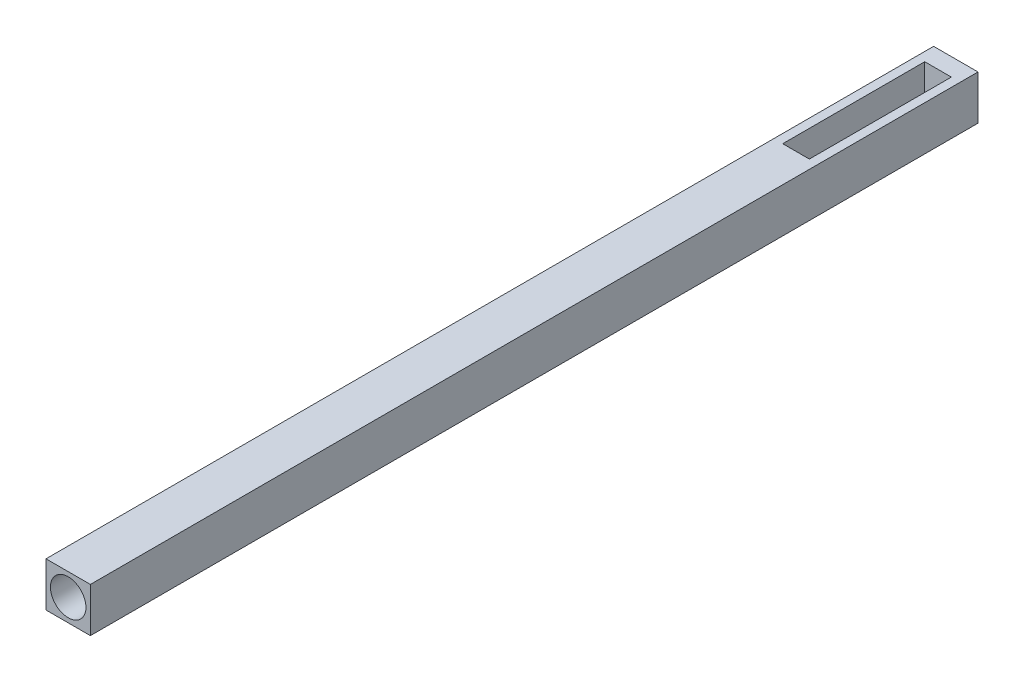
SolidWorks part; units mm, degrees
material "PET"
ref_plane "Front Plane" through (0, 0, 0) normal (0, 0, 1) x (1, 0, 0)
ref_plane "Top Plane" through (0, 0, 0) normal (0, 1, 0) x (1, 0, 0)
ref_plane "Right Plane" through (0, 0, 0) normal (1, 0, 0) x (0, 0, -1)
sketch "Sketch1" plane through (0, 0, 0) normal (0, 1, 0) x (1, 0, 0)
  line L0 (-1.5875, 38.1) -> (1.5875, 25.4) construction
  line L1 (-1.5875, 25.4) -> (1.5875, 25.4) construction
  line L2 (-1.5875, 25.4) -> (-1.5875, -25.4)
  line L3 (-1.5875, -25.4) -> (1.5875, -25.4)
  line L4 (1.5875, 25.4) -> (1.5875, -25.4)
  line L5 (-1.5875, 25.4) -> (1.5875, -25.4) construction
  line L6 (-1.5875, -25.4) -> (1.5875, 25.4) construction
  line L7 (-1.5875, 25.4) -> (1.5875, 25.4) construction
  line L8 (-1.5875, 25.4) -> (-1.5875, 38.1)
  line L9 (-1.5875, 38.1) -> (1.5875, 38.1)
  line L10 (1.5875, 25.4) -> (1.5875, 38.1)
  line L11 (0.9525, 26.67) -> (-0.9525, 26.67)
  line L12 (0.9525, 26.67) -> (0.9525, 36.83)
  line L13 (0.9525, 36.83) -> (-0.9525, 36.83)
  line L14 (-0.9525, 26.67) -> (-0.9525, 36.83)
  line L15 (0.9525, 26.67) -> (-0.9525, 36.83) construction
  line L16 (0.9525, 36.83) -> (-0.9525, 26.67) construction
  line L17 (-1.5875, 25.4) -> (1.5875, 38.1) construction
  point P0 (0, 0)
  point P4 (0, 31.75)
  point P14 (0, 31.75)
  dimension "D1" = 3.175
  dimension "D2" = 50.8
  dimension "D3" = 12.7
  dimension "D4" = 10.16
  dimension "D5" = 1.905
extrude "Boss-Extrude2" add sketch "Sketch1" along normal blind 3.175
sketch "Sketch2" plane through (0, 0, 25.4) normal (0, 0, 1) x (1, 0, 0)
  line L0 (-1.5875, 3.175) -> (1.5875, 0) construction
  line L1 (-1.5875, 0) -> (1.5875, 3.175) construction
  circle A0 centre (0, 1.5875) radius 1.27
  dimension "D1" = 2.54
extrude "Cut-Extrude1" cut sketch "Sketch2" against normal up to surface (52.07 mm away) up to face at (0, 1.5875, -26.67)
